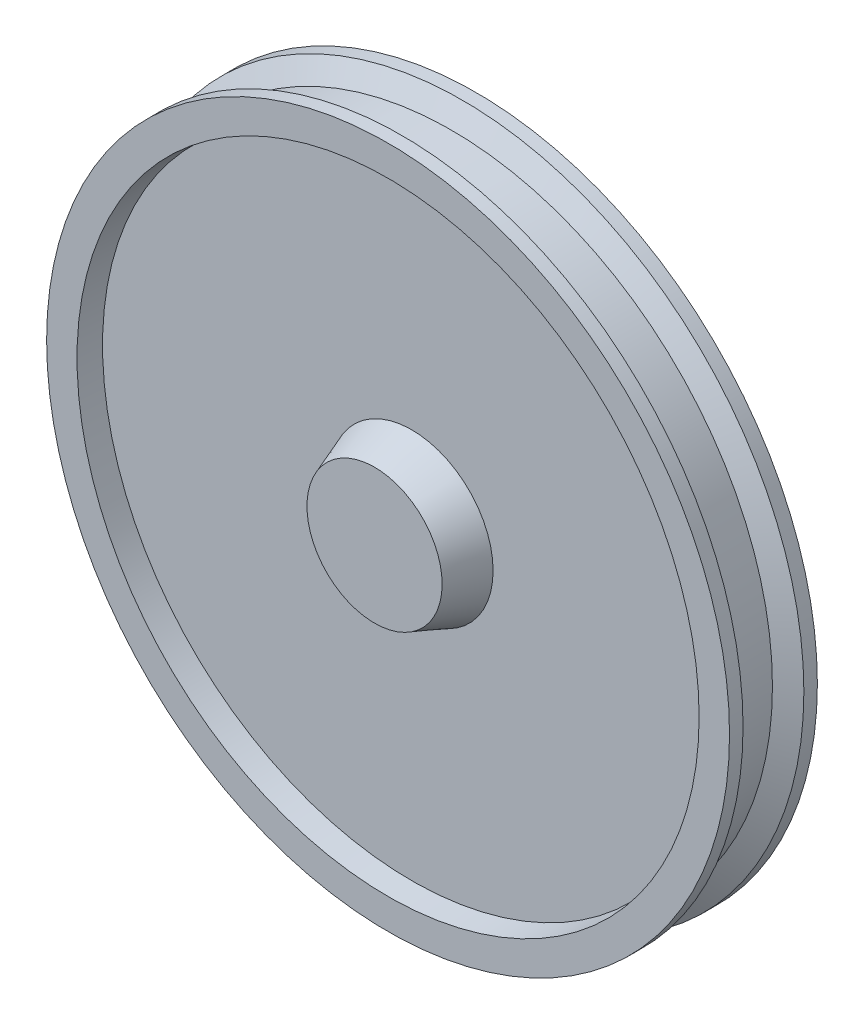
SolidWorks part; units mm, degrees
material "1060 Alloy"
ref_plane "Front Plane" through (0, 0, 0) normal (0, 0, 1) x (1, 0, 0)
ref_plane "Top Plane" through (0, 0, 0) normal (0, 1, 0) x (1, 0, 0)
ref_plane "Right Plane" through (0, 0, 0) normal (1, 0, 0) x (0, 0, -1)
sketch "Sketch1" plane through (0, 0, 0) normal (1, 0, 0) x (0, 0, -1)
  line L0 (0, -475.2546) -> (0, 475.2546) construction
  line L1 (-374.6363, 0) -> (374.6363, 0) construction
  line L2 (-85, 0) -> (-85, 100)
  line L3 (-85, 100) -> (-30, 120.4073)
  line L4 (-30, 120.4073) -> (-30, 457.5)
  line L5 (85, 0) -> (85, 100)
  line L6 (85, 100) -> (30, 120.4073)
  line L7 (30, 120.4073) -> (30, 457.5)
  line L8 (-30, 457.5) -> (-65, 460.2546)
  line L9 (-65, 460.2546) -> (-65, 505.2546)
  line L10 (-65, 505.2546) -> (-45, 505.2546)
  line L11 (-45, 505.2546) -> (-28.5083, 475.2546)
  line L12 (-28.5083, 475.2546) -> (28.5083, 475.2546)
  line L13 (28.5083, 475.2546) -> (45, 505.2546)
  line L14 (45, 505.2546) -> (65, 505.2546)
  line L15 (65, 505.2546) -> (65, 460.2546)
  line L16 (65, 460.2546) -> (30, 457.5)
  line L17 (-85, 0) -> (85, 0)
  point P3 (0, 0)
  point P4 (0, 0)
  point P8 (0, 0)
  point P14 (0.1567, 475.2546)
  point P25 (0, 0)
  dimension "D1" = 100
  dimension "D2" = 170
  dimension "D3" = 60
  dimension "D4" = 457.5
  dimension "D5" = 30
  dimension "D6" = 20
  dimension "D7" = 45
  dimension "D8" = 130
  dimension "D9" = 57.0165
  dimension "D10" = 110.357
revolve "Revolve1" add sketch "Sketch1" angle 360 about L1
